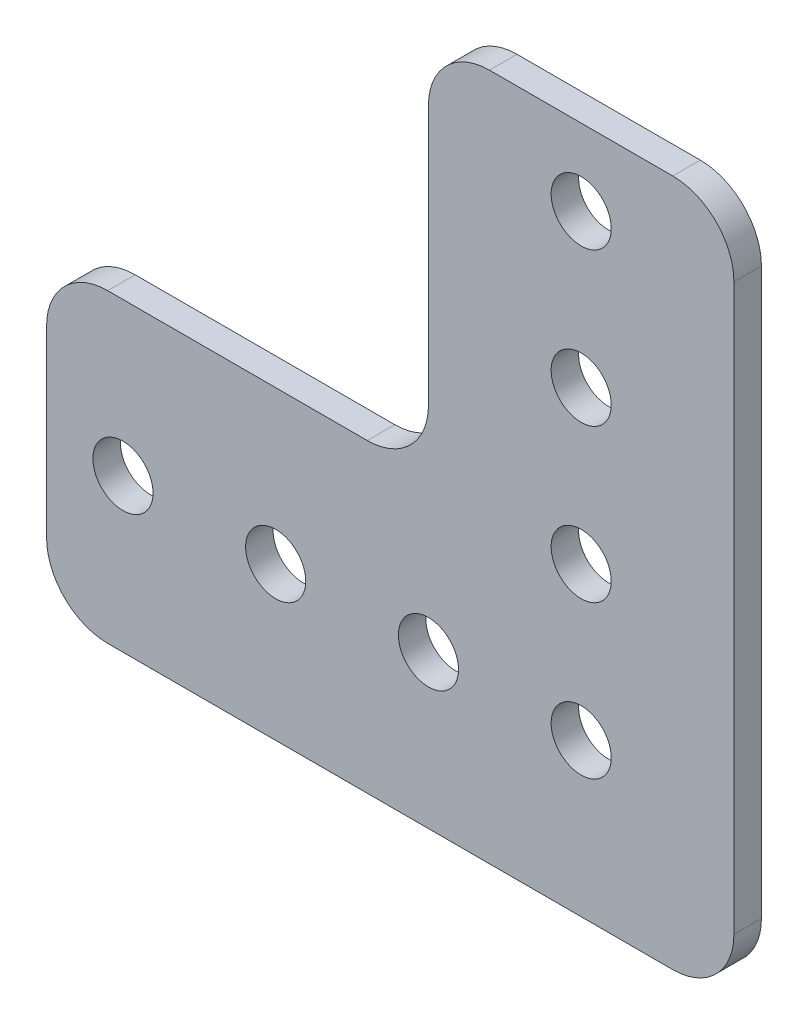
SolidWorks part; units mm, degrees
ref_plane "Front Plane" through (0, 0, 0) normal (0, 0, 1) x (1, 0, 0)
ref_plane "Top Plane" through (0, 0, 0) normal (0, 1, 0) x (1, 0, 0)
ref_plane "Right Plane" through (0, 0, 0) normal (1, 0, 0) x (0, 0, -1)
sketch "Sketch1" plane through (0, 0, 0) normal (0, 0, 1) x (1, 0, 0)
  line L0 (7.62, 577.85) -> (-7.62, 577.85)
  line L1 (12.7, 1181.1) -> (12.7, 520.7) construction
  line L2 (-12.7, 1181.1) -> (-12.7, 520.7) construction
  line L3 (-12.7, 572.77) -> (-12.7, 551.18)
  line L4 (-17.78, 546.1) -> (-39.37, 546.1)
  line L5 (-12.7, 546.1) -> (-317.5, 546.1) construction
  line L6 (-44.45, 541.02) -> (-44.45, 525.78)
  line L7 (-12.7, 520.7) -> (-317.5, 520.7) construction
  line L8 (-39.37, 520.7) -> (7.62, 520.7)
  line L9 (12.7, 525.78) -> (12.7, 572.77)
  circle A0 centre (0, 533.4) radius 2.5
  circle A1 centre (-12.7, 533.4) radius 2.5
  circle A2 centre (-25.4, 533.4) radius 2.5
  circle A3 centre (-38.1, 533.4) radius 2.5
  circle A4 centre (0, 546.1) radius 2.5
  circle A5 centre (0, 558.8) radius 2.5
  circle A6 centre (0, 571.5) radius 2.5
  arc A7 (7.62, 577.85) -> (12.7, 572.77) centre (7.62, 572.77) cw
  arc A8 (-7.62, 577.85) -> (-12.7, 572.77) centre (-7.62, 572.77) ccw
  arc A9 (-39.37, 546.1) -> (-44.45, 541.02) centre (-39.37, 541.02) ccw
  arc A10 (-44.45, 525.78) -> (-39.37, 520.7) centre (-39.37, 525.78) ccw
  arc A11 (-12.7, 551.18) -> (-17.78, 546.1) centre (-17.78, 551.18) cw
  arc A12 (7.62, 520.7) -> (12.7, 525.78) centre (7.62, 525.78) ccw
  point P6 (-44.45, 533.4)
  point P34 (12.7, 577.85)
  point P37 (-12.7, 577.85)
  point P40 (-44.45, 546.1)
  point P43 (-44.45, 520.7)
  point P46 (-12.7, 546.1)
  point P49 (12.7, 520.7)
  dimension "D5" = 5.08
  dimension "D1" = 57.15
  dimension "D2" = 57.15
  dimension "D3" = 4
  dimension "D4" = 4
extrude "Boss-Extrude1" add sketch "Sketch1" along normal blind 2.286
